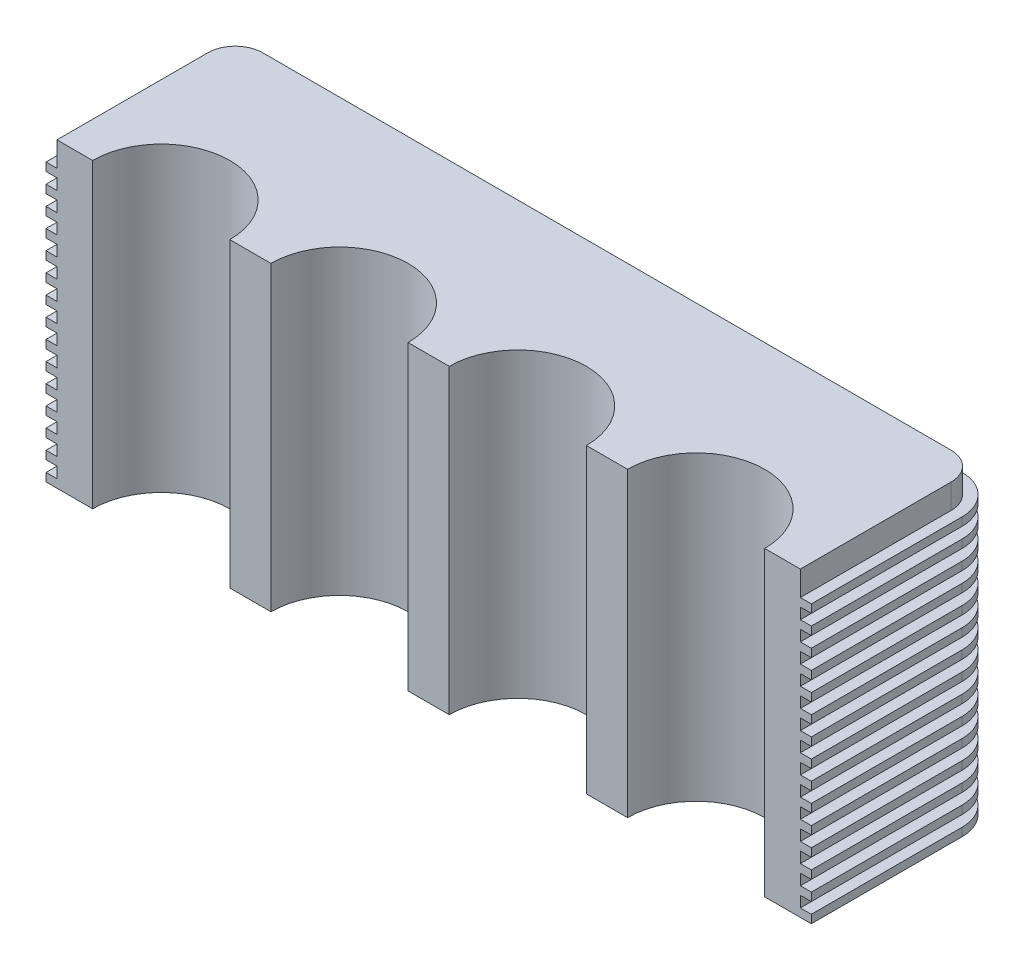
SolidWorks part; units mm, degrees
ref_plane "Front Plane" through (0, 0, 0) normal (0, 0, 1) x (1, 0, 0)
ref_plane "Top Plane" through (0, 0, 0) normal (0, 1, 0) x (1, 0, 0)
ref_plane "Right Plane" through (0, 0, 0) normal (1, 0, 0) x (0, 0, -1)
sketch "Sketch1" plane through (0, 0, 0) normal (0, 1, 0) x (1, 0, 0)
  line L0 (135.5, 0) -> (135.5, 65) construction
  line L1 (0, 0) -> (13, 0)
  line L2 (0, 0) -> (0, 55)
  line L3 (10, 65) -> (261, 65)
  line L4 (271, 0) -> (271, 55)
  line L5 (258, 0) -> (271, 0)
  line L6 (193, 0) -> (208, 0)
  line L7 (128, 0) -> (143, 0)
  line L8 (63, 0) -> (78, 0)
  arc A0 (271, 55) -> (261, 65) centre (261, 55) ccw
  arc A1 (0, 55) -> (10, 65) centre (10, 55) cw
  arc A2 (258, 0) -> (208, 0) centre (233, 0) ccw
  arc A3 (193, 0) -> (143, 0) centre (168, 0) ccw
  arc A4 (13, 0) -> (63, 0) centre (38, 0) cw
  arc A5 (78, 0) -> (128, 0) centre (103, 0) cw
  dimension "D1" = 10
  dimension "D4" = 25
  dimension "D6" = 15
  dimension "D7" = 25
  dimension "D2" = 271
  dimension "D3" = 65
  dimension "D5" = 13
extrude "Boss-Extrude1" add sketch "Sketch1" along normal blind 110
sketch "Sketch2" plane through (0, 0, 0) normal (0, 1, 0) x (1, 0, 0)
  line L0 (275, 0) -> (275, 55)
  line L1 (261, 69) -> (10, 69)
  line L2 (-4, 55) -> (-4, 0)
  line L3 (271, 0) -> (275, 0)
  line L4 (0, 0) -> (-4, 0)
  line L8 (0, 55) -> (0, 0)
  line L9 (0, 0) -> (13, 0)
  line L10 (63, 0) -> (78, 0)
  line L11 (128, 0) -> (143, 0)
  line L12 (193, 0) -> (208, 0)
  line L13 (258, 0) -> (271, 0)
  line L14 (271, 0) -> (271, 55)
  line L15 (261, 65) -> (10, 65)
  line L16 (0, 55) -> (0, 0)
  line L22 (271, 0) -> (271, 55)
  line L23 (261, 65) -> (10, 65)
  arc A0 (275, 55) -> (261, 69) centre (261, 55) ccw
  arc A1 (10, 69) -> (-4, 55) centre (10, 55) ccw
  arc A6 (63, 0) -> (13, 0) centre (38, 0) ccw
  arc A7 (128, 0) -> (78, 0) centre (103, 0) ccw
  arc A8 (193, 0) -> (143, 0) centre (168, 0) ccw
  arc A9 (258, 0) -> (208, 0) centre (233, 0) ccw
  arc A10 (271, 55) -> (261, 65) centre (261, 55) ccw
  arc A11 (10, 65) -> (0, 55) centre (10, 55) ccw
  arc A16 (271, 55) -> (261, 65) centre (261, 55) ccw
  arc A17 (10, 65) -> (0, 55) centre (10, 55) ccw
  dimension "D1" = 0
  dimension "D2" = 4
extrude "Boss-Extrude2" add sketch "Sketch2" along normal blind 3
pattern_linear "LPattern1" count 15 spacing 7 along (0, 1, 0) of "Boss-Extrude2"
